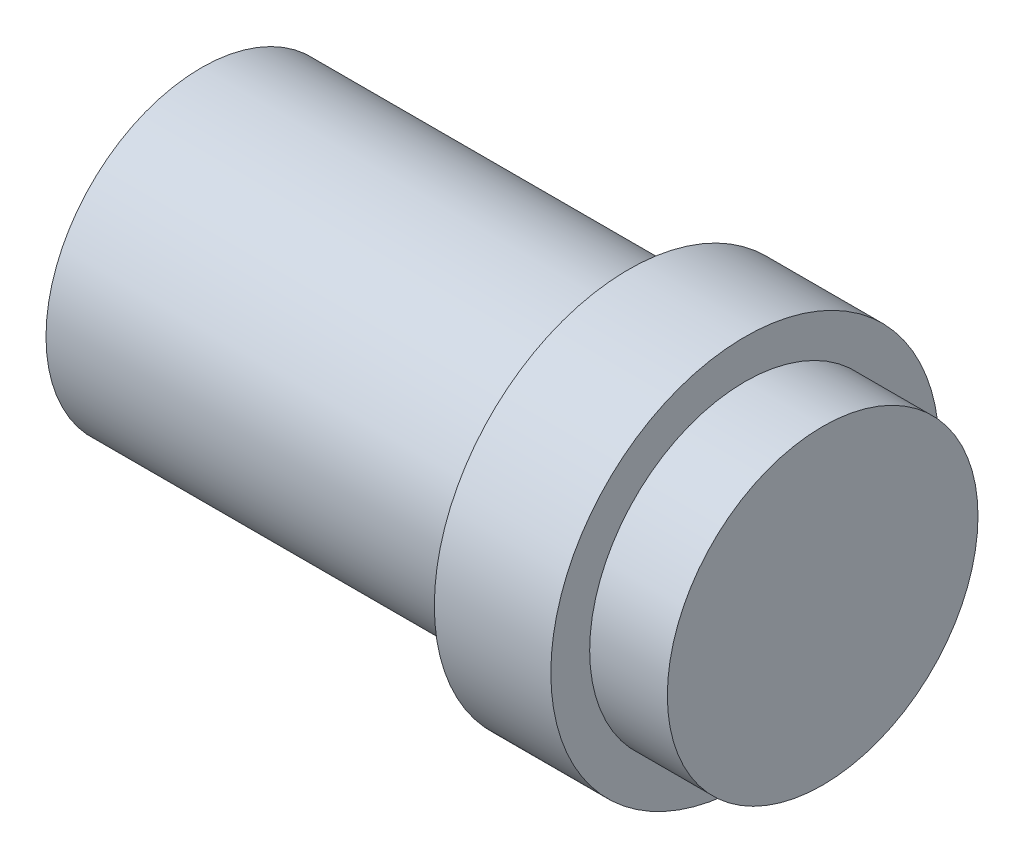
SolidWorks part; units mm, degrees
ref_plane "前视基准面" through (0, 0, 0) normal (0, 0, 1) x (1, 0, 0)
ref_plane "上视基准面" through (0, 0, 0) normal (0, 1, 0) x (1, 0, 0)
ref_plane "右视基准面" through (0, 0, 0) normal (1, 0, 0) x (0, 0, -1)
sketch "草图1" plane through (0, 0, 0) normal (0, 0, 1) x (1, 0, 0)
  line L0 (-84.796, 0) -> (66.6524, 0) construction
  line L1 (-25, 0) -> (-25, 8)
  line L2 (0, 69.6763) -> (0, -59.0926) construction
  line L3 (-25, 8) -> (-3, 8)
  line L4 (-3, 8) -> (-3, 10)
  line L5 (-3, 10) -> (3, 10)
  line L6 (3, 10) -> (3, 8)
  line L7 (3, 8) -> (7, 8)
  line L8 (7, 8) -> (7, 0)
  line L9 (7, 0) -> (-25, 0)
  dimension "D1" = 6
  dimension "D2" = 22
  dimension "D3" = 4
  dimension "D4" = 8
  dimension "D5" = 2
revolve "旋转1" add sketch "草图1" angle 360 about L0
